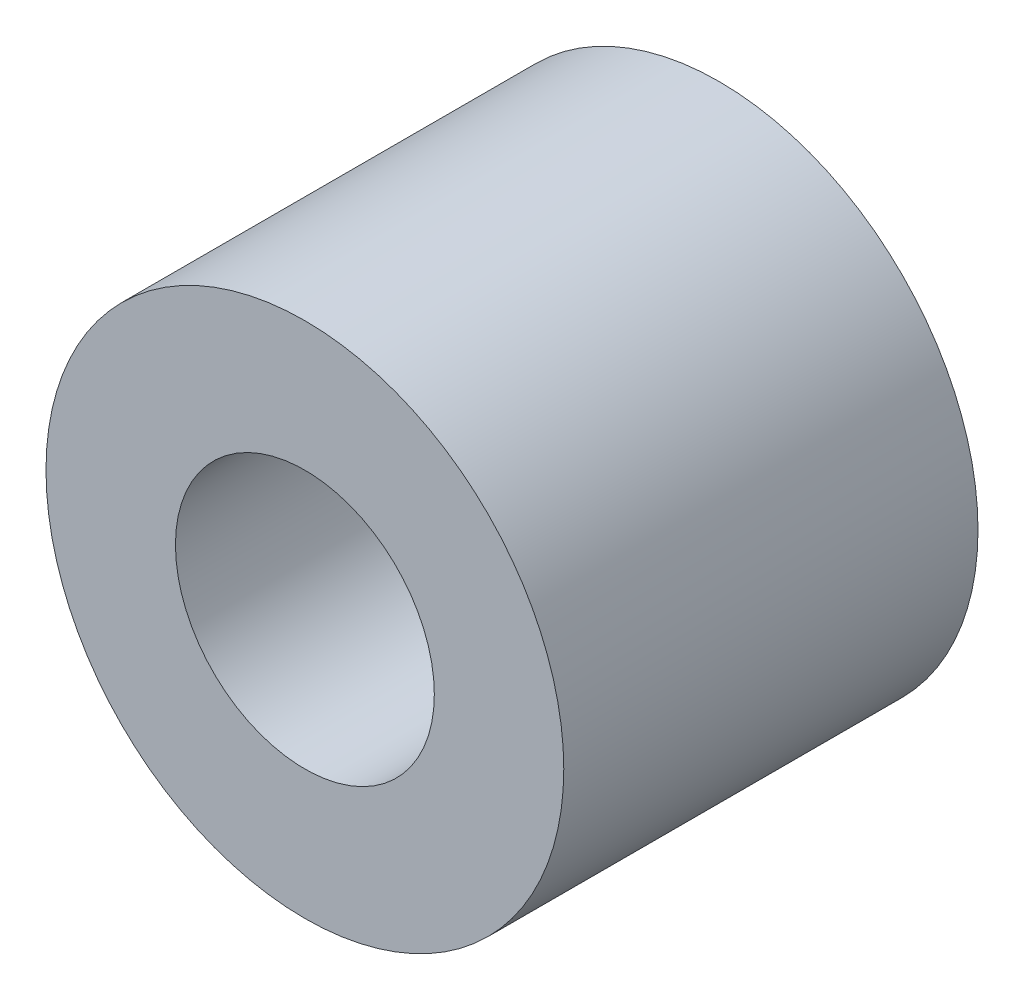
SolidWorks part; units mm, degrees
ref_plane "Front Plane" through (0, 0, 0) normal (0, 0, 1) x (1, 0, 0)
ref_plane "Top Plane" through (0, 0, 0) normal (0, 1, 0) x (1, 0, 0)
ref_plane "Right Plane" through (0, 0, 0) normal (1, 0, 0) x (0, 0, -1)
sketch "Sketch1" plane through (0, 0, 0) normal (0, 0, 1) x (1, 0, 0)
  circle A0 centre (0, 15.875) radius 3.175
  circle A1 centre (0, 15.875) radius 6.35
extrude "Boss-Extrude1" add sketch "Sketch1" along normal blind 10.16
